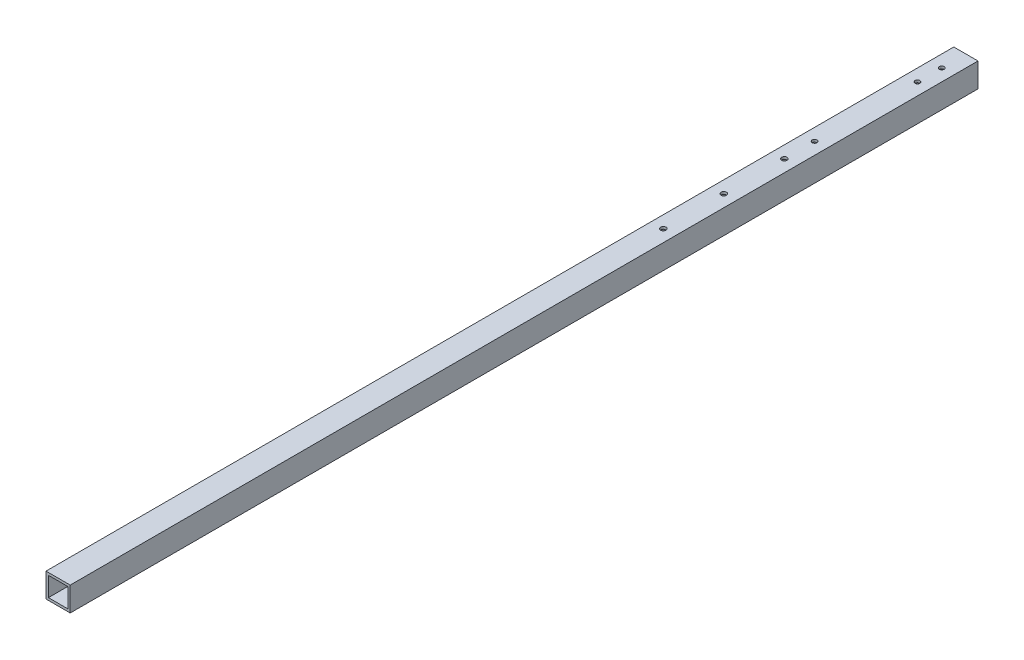
SolidWorks part; units mm, degrees
ref_plane "前视基准面" through (0, 0, 0) normal (0, 0, 1) x (1, 0, 0)
ref_plane "上视基准面" through (0, 0, 0) normal (0, 1, 0) x (1, 0, 0)
ref_plane "右视基准面" through (0, 0, 0) normal (1, 0, 0) x (0, 0, -1)
sketch "草图1" plane through (0, 0, 0) normal (0, 0, 1) x (1, 0, 0)
  line L1 (-10, 10) -> (10, 10)
  line L2 (-10, 10) -> (-10, -10)
  line L3 (-10, -10) -> (10, -10)
  line L4 (10, 10) -> (10, -10)
  line L5 (-10, 10) -> (10, -10) construction
  line L6 (-10, -10) -> (10, 10) construction
  line L7 (-8, 8) -> (8, 8)
  line L8 (-8, 8) -> (-8, -8)
  line L9 (-8, -8) -> (8, -8)
  line L10 (8, 8) -> (8, -8)
  line L11 (-8, 8) -> (8, -8) construction
  line L12 (-8, -8) -> (8, 8) construction
  point P0 (0, 0)
  point P5 (0, 0)
  dimension "D1" = 20
  dimension "D2" = 16
  dimension "D3" = 16
extrude "凸台-拉伸1" add sketch "草图1" along normal mid plane 750
sketch "草图2" plane through (0, 10, 0) normal (0, 1, 0) x (1, 0, 0)
  circle A0 centre (0, 385) radius 2 construction
  circle A1 centre (0, 355) radius 2 construction
  circle A3 centre (0, 250) radius 2 construction
  circle A4 centre (0, 385) radius 2
  circle A5 centre (0, 355) radius 2
  circle A7 centre (0, 250) radius 2
  circle A8 centre (0, 335) radius 2 construction
  circle A9 centre (0, 335) radius 2
extrude "切除-拉伸1" cut sketch "草图2" against normal through all
sketch "草图3" plane through (0, 10, 0) normal (0, 1, 0) x (1, 0, 0)
  circle A0 centre (0, 125) radius 2.25 construction
  circle A1 centre (0, 175) radius 2.25 construction
  circle A2 centre (0, 225) radius 2.25 construction
  circle A3 centre (0, 125) radius 2.25
  circle A4 centre (0, 175) radius 2.25
  circle A5 centre (0, 225) radius 2.25
extrude "切除-拉伸2" cut sketch "草图3" against normal through all
sketch "草图4" plane through (10, 0, 0) normal (1, 0, 0) x (0, 0, -1)
